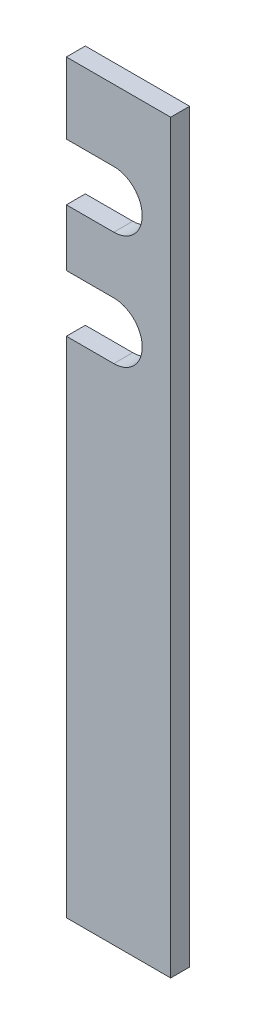
SolidWorks part; units mm, degrees
ref_plane "Front Plane" through (0, 0, 0) normal (0, 0, 1) x (1, 0, 0)
ref_plane "Top Plane" through (0, 0, 0) normal (0, 1, 0) x (1, 0, 0)
ref_plane "Right Plane" through (0, 0, 0) normal (1, 0, 0) x (0, 0, -1)
sketch "Sketch1" plane through (0, 0, 0) normal (0, 0, 1) x (1, 0, 0)
  line L1 (2.75, -19.65) -> (-2.75, -19.65)
  line L2 (2.75, -19.65) -> (2.75, 19.65)
  line L3 (2.75, 19.65) -> (-2.75, 19.65)
  line L4 (-2.75, -19.65) -> (-2.75, 19.65)
  line L5 (2.75, -19.65) -> (-2.75, 19.65) construction
  line L6 (2.75, 19.65) -> (-2.75, -19.65) construction
  point P0 (0, 0)
  dimension "D1" = 39.3
  dimension "D2" = 5.5
extrude "Boss-Extrude1" add sketch "Sketch1" along normal blind 1
sketch "Sketch2" plane through (0, 0, 1) normal (0, 0, 1) x (1, 0, 0)
  line L0 (-2.75, 19.65) -> (-2.75, -19.65) construction
  line L1 (2.75, 19.65) -> (-2.75, 19.65) construction
  line L3 (-0.25, 15.9) -> (-2.75, 15.9)
  line L4 (-0.25, 15.9) -> (-0.25, 12.9)
  line L5 (-0.25, 12.9) -> (-2.75, 12.9)
  line L6 (-2.75, 15.9) -> (-2.75, 12.9)
  line L7 (-0.25, 9.9) -> (-2.75, 9.9)
  line L8 (-0.25, 9.9) -> (-0.25, 6.9)
  line L9 (-0.25, 6.9) -> (-2.75, 6.9)
  line L10 (-2.75, 9.9) -> (-2.75, 6.9)
  circle A0 centre (-0.25, 14.4) radius 1.5
  circle A1 centre (-0.25, 8.4) radius 1.5
  line M7 (-2.75, 19.65) -> (-2.75, -19.65)
  dimension "D1" = 3
  dimension "D5" = 3
  dimension "D2" = 2.5
  dimension "D3" = 5.25
  dimension "D4" = 2.5
  dimension "D6" = 11.25
  dimension "D7" = 3
  dimension "D8" = 3
extrude "Cut-Extrude2" cut sketch "Sketch2" against normal blind 1 contours A0 L3 L5 M7 | L4 A0 | L4 A0 | A1 L7 L9 M7 | L8 A1 | L8 A1
